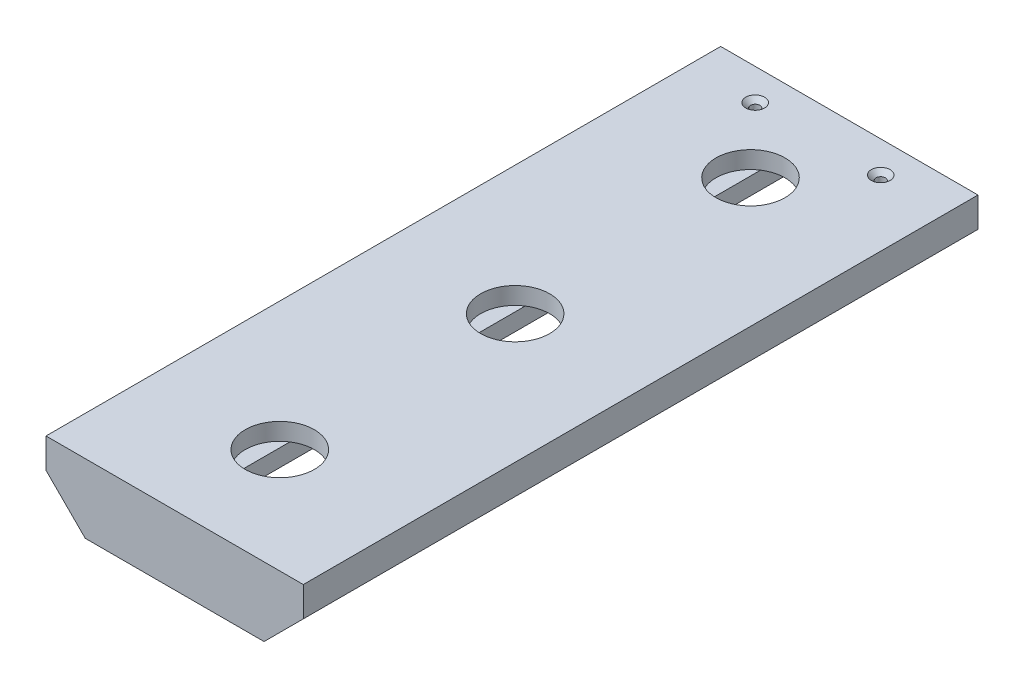
SolidWorks part; units mm, degrees
ref_plane "Płaszczyzna przednia" through (0, 0, 0) normal (0, 0, 1) x (1, 0, 0)
ref_plane "Płaszczyzna górna" through (0, 0, 0) normal (0, 1, 0) x (1, 0, 0)
ref_plane "Płaszczyzna prawa" through (0, 0, 0) normal (1, 0, 0) x (0, 0, -1)
sketch "Sketch1" plane through (0, 0, 0) normal (0, 0, 1) x (1, 0, 0)
  line L0 (5.2402, 23.9115) -> (14.2402, 14.9115)
  line L1 (5.2402, 24.9115) -> (75.2402, 24.9115)
  line L2 (5.2402, 24.9115) -> (5.2402, 23.9115)
  line L3 (14.2402, 14.9115) -> (66.2402, 14.9115)
  line L4 (75.2402, 24.9115) -> (75.2402, 23.9115)
  line L5 (66.2402, 14.9115) -> (75.2402, 23.9115)
  line L6 (-0.7598, 30.9115) -> (-0.7598, 21.4263)
  line L7 (-0.7598, 21.4263) -> (11.7549, 8.9115)
  line L8 (11.7549, 8.9115) -> (23.2402, 8.9115)
  line L9 (68.7255, 8.9115) -> (81.2402, 21.4263)
  line L10 (81.2402, 30.9115) -> (81.2402, 21.4263)
  line L11 (-0.7598, 30.9115) -> (81.2402, 30.9115)
  line L12 (40.2402, 8.0032) -> (40.2402, 58.733) construction
  line L13 (40.2402, 8.0032) -> (14.2402, 14.9115) construction
  line L14 (40.2402, 8.0032) -> (66.2402, 14.9115) construction
  line L15 (14.2402, 14.9115) -> (23.2402, 14.9115) construction
  line L16 (23.2402, 14.9115) -> (23.2402, 8.9115)
  line L17 (57.2402, 8.9115) -> (68.7255, 8.9115)
  line L18 (57.2402, 14.9115) -> (57.2402, 8.9115)
  line L19 (11.7549, 8.9115) -> (68.7255, 8.9115) construction
  line L20 (14.0331, 14.4115) -> (66.4473, 14.4115)
  line L21 (66.4473, 14.4115) -> (75.7402, 23.7044)
  line L22 (75.7402, 25.4115) -> (75.7402, 23.7044)
  line L23 (4.7402, 25.4115) -> (75.7402, 25.4115)
  line L24 (4.7402, 25.4115) -> (4.7402, 23.7044)
  line L25 (4.7402, 23.7044) -> (14.0331, 14.4115)
  point P1 (75.2402, 14.9115)
  point P2 (5.2402, 14.9115)
  point P21 (0, 0)
  dimension "D1" = 70
  dimension "D2" = 10
  dimension "D3" = 1
  dimension "D4" = 6
  dimension "D5" = 9
  dimension "D6" = 0.5
extrude "Boss-Extrude2" add sketch "Sketch1" along normal blind 213 contours L3 L18 L17 L9 L10 L11 L6 L7 L8 L16 L0 L2 L1 L4 L5
sketch "Sketch3" plane through (0, 0, 213) normal (0, 0, 1) x (1, 0, 0)
  line L0 (-0.7598, 30.9115) -> (-0.7598, 21.4263)
  line L1 (-0.7598, 21.4263) -> (11.7549, 8.9115)
  line L2 (11.7549, 8.9115) -> (23.2402, 8.9115)
  line L3 (23.2402, 8.9115) -> (57.2402, 8.9115)
  line L4 (57.2402, 8.9115) -> (68.7255, 8.9115)
  line L5 (68.7255, 8.9115) -> (81.2402, 21.4263)
  line L6 (81.2402, 21.4263) -> (81.2402, 30.9115)
  line L7 (81.2402, 30.9115) -> (-0.7598, 30.9115)
extrude "Boss-Extrude4" add sketch "Sketch3" along normal blind 2
sketch "Sketch4" plane through (0, 30.9115, 0) normal (0, 1, 0) x (1, 0, 0)
  line L0 (40.2402, 13.8529) -> (40.2402, -95.7525) construction
  line L4 (-0.7598, 0) -> (40.2402, 13.8529) construction
  line L5 (40.2402, 13.8529) -> (81.2402, 0) construction
  line L7 (20.2402, 0) -> (60.2402, 0) construction
  line L8 (60.2402, 0) -> (60.2402, -10) construction
  line L9 (-0.7598, 0) -> (81.2402, 0) construction
  line L10 (20.2402, 0) -> (20.2402, -10) construction
  circle A0 centre (60.2402, -10) radius 1.5
  circle A1 centre (20.2402, -10) radius 1.5
  point P16 (40.2402, 0)
  dimension "D3" = 3
  dimension "D1" = 20
  dimension "D2" = 10
extrude "Cut-Extrude1" cut sketch "Sketch4" against normal blind 10
chamfer "Chamfer2" distance 1.5 angle 45 2 edges at (58.7402, 30.9115, 10) (21.7402, 30.9115, 10)
sketch "Sketch5" plane through (0, 30.9115, 0) normal (0, 1, 0) x (1, 0, 0)
  line L0 (40.2402, 0) -> (40.2402, -95.6331) construction
  line L1 (-0.7598, 0) -> (81.2402, 0) construction
  circle A0 centre (40.2402, -31.5) radius 11
  circle A1 centre (40.2402, -106.5) radius 11
  circle A2 centre (40.2402, -181.5) radius 11
  point P5 (40.2402, 0)
  dimension "D2" = 22
  dimension "D1" = 31.5
  dimension "D3" = 3
extrude "Cut-Extrude2" cut sketch "Sketch5" against normal blind 52
